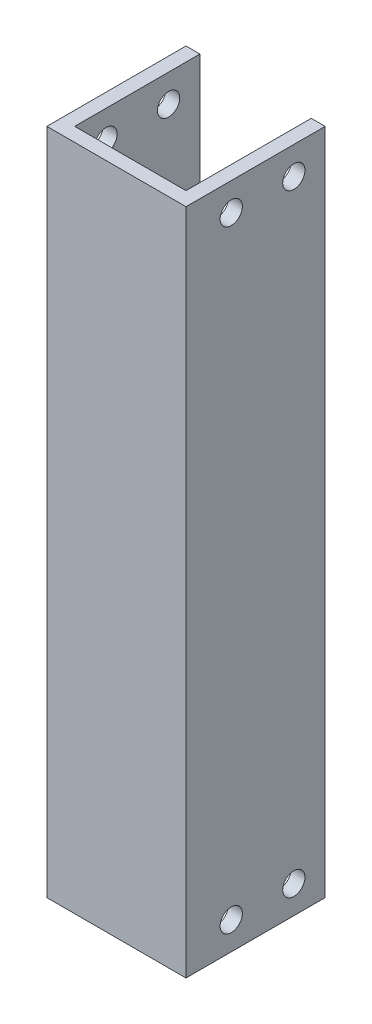
SolidWorks part; units mm, degrees
ref_plane "Front Plane" through (0, 0, 0) normal (0, 0, 1) x (1, 0, 0)
ref_plane "Top Plane" through (0, 0, 0) normal (0, 1, 0) x (1, 0, 0)
ref_plane "Right Plane" through (0, 0, 0) normal (1, 0, 0) x (0, 0, -1)
sketch "Sketch1" plane through (0, 0, 0) normal (0, 1, 0) x (1, 0, 0)
  line L0 (0, 0) -> (31.75, 0)
  line L1 (31.75, 0) -> (31.75, 31.75)
  line L2 (31.75, 31.75) -> (28.575, 31.75)
  line L3 (0, 0) -> (0, 31.75)
  line L4 (0, 31.75) -> (3.175, 31.75)
  line L5 (3.175, 31.75) -> (3.175, 3.175)
  line L6 (3.175, 3.175) -> (28.575, 3.175)
  line L7 (28.575, 3.175) -> (28.575, 31.75)
extrude "Boss-Extrude1" add sketch "Sketch1" along normal blind 152.4
sketch "Sketch2" plane through (31.75, 0, 0) normal (1, 0, 0) x (0, 0, -1)
  circle A0 centre (24.6062, 6.35) radius 2.54
  circle A1 centre (10.3188, 6.35) radius 2.54
  circle A2 centre (24.6062, 146.05) radius 2.54
  circle A3 centre (10.3188, 146.05) radius 2.54
extrude "Cut-Extrude2" cut sketch "Sketch2" against normal blind 31.75
